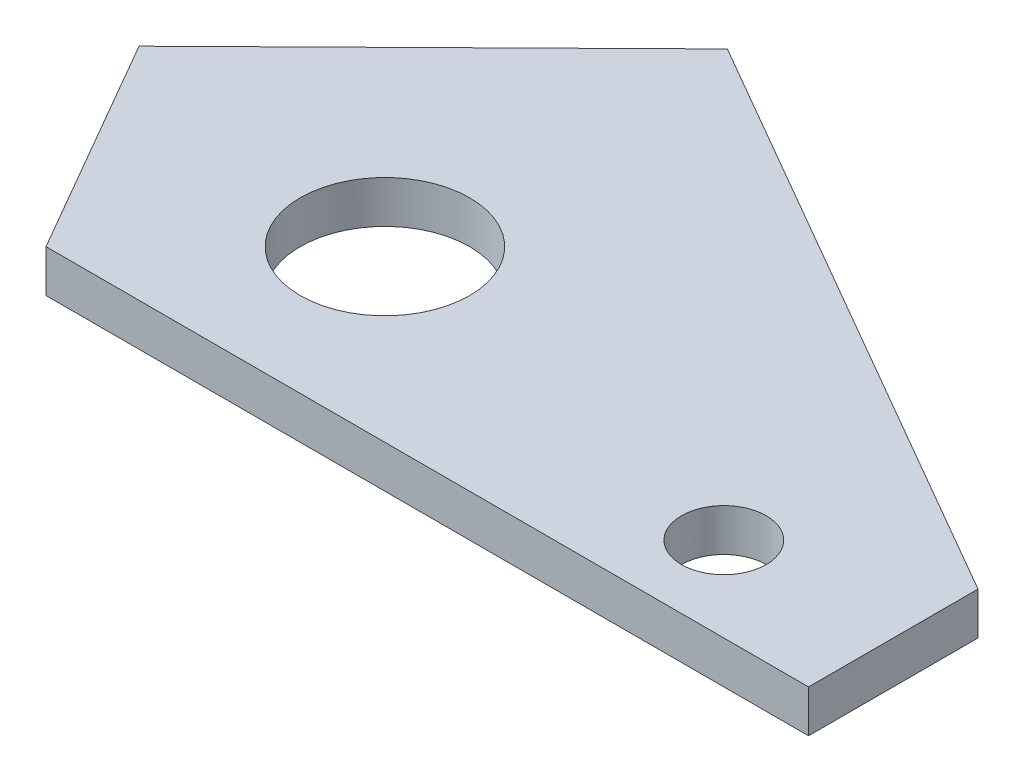
SolidWorks part; units mm, degrees
ref_plane "Front Plane" through (0, 0, 0) normal (0, 0, 1) x (1, 0, 0)
ref_plane "Top Plane" through (0, 0, 0) normal (0, 1, 0) x (1, 0, 0)
ref_plane "Right Plane" through (0, 0, 0) normal (1, 0, 0) x (0, 0, -1)
sketch "Sketch1" plane through (0, 0, 0) normal (0, 1, 0) x (1, 0, 0)
  line L0 (-114.3, 0) -> (-133.35, 32.9956)
  line L1 (0, 0) -> (-114.3, 0)
  line L2 (0, 0) -> (0, 25.4)
  line L3 (0, 25.4) -> (-114.3, 25.4)
  line L4 (-114.3, 0) -> (-114.3, 25.4)
  line L5 (-133.35, 32.9956) -> (-88.9, 76.7264)
  line L6 (-88.9, 76.7264) -> (0, 25.4)
  dimension "D1" = 114.3
  dimension "D2" = 25.4
  dimension "D3" = 38.1
  dimension "D4" = 30
  dimension "D5" = 30
  dimension "D6" = 88.9
extrude "Boss-Extrude1" add sketch "Sketch1" along normal blind 6.35 contours L4 L1 L2 L3 | L6 L5 L0 L4 L3
sketch "Sketch2" plane through (0, 0, 0) normal (0, -1, 0) x (1, 0, 0)
  line L0 (0, 0) -> (-114.3, 0) construction
  line L2 (0, 0) -> (0, -25.4) construction
  circle A0 centre (-88.9, -25.4) radius 12.7
  circle A1 centre (-25.4, -12.7) radius 6.35
  dimension "D1" = 25.4
  dimension "D2" = 12.7
  dimension "D3" = 25.4
  dimension "D4" = 88.9
  dimension "D5" = 25.4
  dimension "D6" = 12.7
extrude "Cut-Extrude1" cut sketch "Sketch2" against normal up to next
